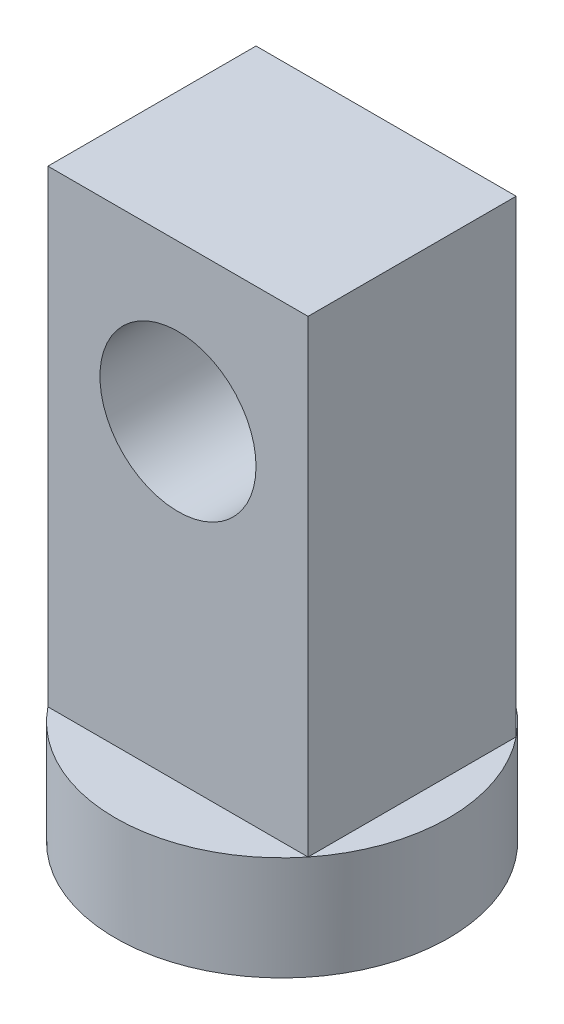
SolidWorks part; units mm, degrees
ref_plane "Front Plane" through (0, 0, 0) normal (0, 0, 1) x (1, 0, 0)
ref_plane "Top Plane" through (0, 0, 0) normal (0, 1, 0) x (1, 0, 0)
ref_plane "Right Plane" through (0, 0, 0) normal (1, 0, 0) x (0, 0, -1)
sketch "Sketch2" plane through (0, 0, 0) normal (0, 0, 1) x (1, 0, 0)
  line L0 (0, 0) -> (0, -25) construction
  line L1 (0, 0) -> (0, 30) construction
  line L2 (-25, -80) -> (25, -80)
  line L3 (-25, -80) -> (-25, 30)
  line L4 (-25, 30) -> (25, 30)
  line L5 (25, -80) -> (25, 30)
  line L6 (-25, -80) -> (25, 30) construction
  line L7 (-25, 30) -> (25, -80) construction
  circle A0 centre (0, 0) radius 15
  dimension "D1" = 30
  dimension "D2" = 30
  dimension "D3" = 50
  dimension "D4" = 80
extrude "Boss-Extrude1" add sketch "Sketch2" along normal mid plane 40
sketch "Sketch3" plane through (0, -80, 0) normal (0, -1, 0) x (1, 0, 0)
  circle A0 centre (0, 0) radius 32.0156
extrude "Boss-Extrude2" add sketch "Sketch3" against normal blind 20
